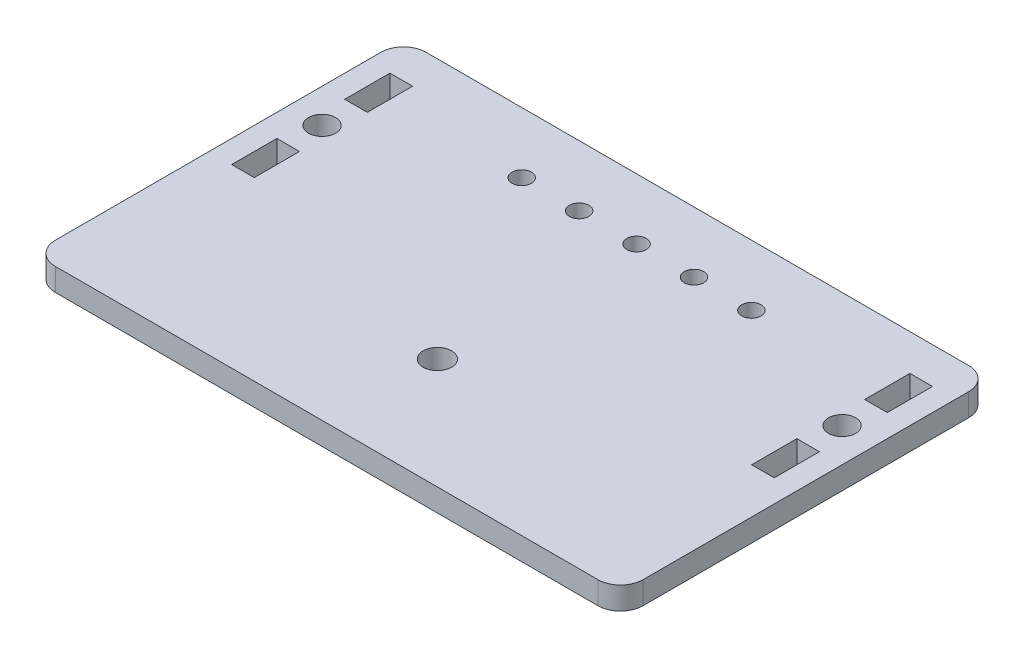
SolidWorks part; units mm, degrees
ref_plane "Front Plane" through (0, 0, 0) normal (0, 0, 1) x (1, 0, 0)
ref_plane "Top Plane" through (0, 0, 0) normal (0, 1, 0) x (1, 0, 0)
ref_plane "Right Plane" through (0, 0, 0) normal (1, 0, 0) x (0, 0, -1)
sketch "Sketch1" plane through (0, 0, 0) normal (0, 1, 0) x (1, 0, 0)
  line L1 (-65, 25) -> (65, 25)
  line L2 (-65, 25) -> (-65, -25)
  line L3 (-65, -25) -> (65, -25)
  line L4 (65, 25) -> (65, -25)
  line L5 (-65, 25) -> (65, -25) construction
  line L6 (-65, -25) -> (65, 25) construction
  point P0 (0, 0)
  dimension "D1" = 130
  dimension "D2" = 50
extrude "Boss-Extrude1" add sketch "Sketch1" along normal blind 5
sketch "Sketch2" plane through (0, 0, -25) normal (0, 0, -1) x (-1, 0, 0)
  line L4 (-65, 0) -> (65, 0)
  line L5 (65, 0) -> (65, 5)
  line L6 (65, 5) -> (-65, 5)
  line L7 (-65, 5) -> (-65, 0)
  line L8 (-65, 0) -> (65, 0)
  line L9 (65, 0) -> (65, 5)
  line L10 (65, 5) -> (-65, 5)
  line L11 (-65, 5) -> (-65, 0)
  dimension "D1" = 0
extrude "Boss-Extrude2" add sketch "Sketch2" along normal blind 32
sketch "Sketch3" plane through (0, 5, 0) normal (0, 1, 0) x (1, 0, 0)
  line L0 (-57.5, 24) -> (-57.5, 39) construction
  line L1 (0, 49.5) -> (0, -17.5) construction
  line L2 (57.5, 24) -> (57.5, 39) construction
  line L3 (55, 49) -> (55, 39)
  line L5 (-60, 24) -> (-55, 24)
  line L6 (-60, 24) -> (-60, 14)
  line L7 (-60, 14) -> (-55, 14)
  line L8 (57.5, -17.5) -> (57.5, 49.5)
  line L9 (57.5, 49.5) -> (-57.5, 49.5)
  line L10 (-57.5, 49.5) -> (-57.5, -17.5)
  line L11 (-57.5, -17.5) -> (57.5, -17.5)
  line L12 (57.5, -17.5) -> (57.5, 49.5) construction
  line L13 (57.5, 49.5) -> (-57.5, 49.5) construction
  line L14 (-57.5, 49.5) -> (-57.5, -17.5) construction
  line L15 (-57.5, -17.5) -> (57.5, -17.5) construction
  line L16 (-55, 24) -> (-55, 14)
  line L17 (60, 39) -> (55, 39)
  line L18 (-60, 49) -> (-55, 49)
  line L19 (-60, 49) -> (-60, 39)
  line L20 (-60, 39) -> (-55, 39)
  line L21 (-55, 49) -> (-55, 39)
  line L22 (60, 49) -> (60, 39)
  line L23 (60, 49) -> (55, 49)
  line L24 (55, 24) -> (55, 14)
  line L25 (60, 14) -> (55, 14)
  line L26 (60, 24) -> (60, 14)
  line L27 (60, 24) -> (55, 24)
  line L28 (-65, 57) -> (65, 57) construction
  circle A0 centre (-57.5, 31.5) radius 3
  circle A1 centre (57.5, 31.5) radius 3
  dimension "D6" = 6
  dimension "D1" = 7.5
  dimension "D2" = 10
  dimension "D3" = 5
  dimension "D4" = 8
  dimension "D5" = 35
extrude "Cut-Extrude1" cut sketch "Sketch3" against normal blind 10
fillet "Fillet1" radius 5 4 edges at (65, 2.5, -57) (-65, 2.5, 25) (65, 2.5, 25) (-65, 2.5, -57)
sketch "Sketch4" plane through (0, 5, 0) normal (0, 1, 0) x (1, 0, 0)
  line L1 (0, 57) -> (0, -25) construction
  line L2 (-60, 57) -> (60, 57) construction
  line L3 (-60, -25) -> (60, -25) construction
  circle A0 centre (0, -0.5) radius 3.15
  circle A1 centre (25.4, 43.55) radius 2.15
  circle A2 centre (-25.4, 43.55) radius 2.15
  circle A3 centre (-12.7, 43.55) radius 2.15
  circle A4 centre (12.7, 43.55) radius 2.15
  circle A5 centre (0, 43.55) radius 2.15
  dimension "D1" = 6.3
  dimension "D2" = 4.3
  dimension "D3" = 12.7
  dimension "D4" = 4.3
extrude "Cut-Extrude2" cut sketch "Sketch4" against normal up to next
